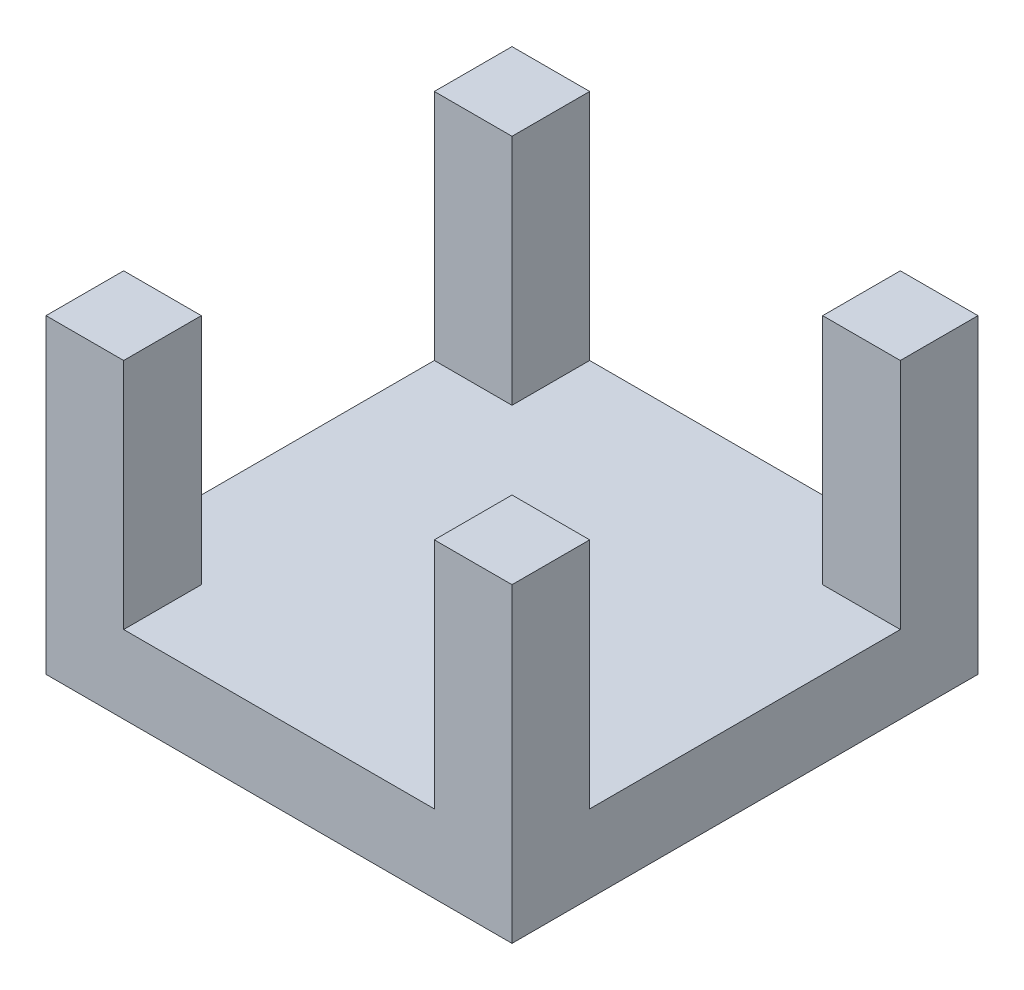
SolidWorks part; units mm, degrees
ref_plane "前视基准面" through (0, 0, 0) normal (0, 0, 1) x (1, 0, 0)
ref_plane "上视基准面" through (0, 0, 0) normal (0, 1, 0) x (1, 0, 0)
ref_plane "右视基准面" through (0, 0, 0) normal (1, 0, 0) x (0, 0, -1)
other "Configuration Table"
sketch "草图1" plane through (0, 0, 0) normal (0, 1, 0) x (1, 0, 0)
  line L1 (-300, 300) -> (300, 300)
  line L2 (-300, 300) -> (-300, -300)
  line L3 (-300, -300) -> (300, -300)
  line L4 (300, 300) -> (300, -300)
  dimension "D1" = 600
  dimension "D2" = 600
  dimension "D3" = 300
  dimension "D4" = 300
extrude "凸台-拉伸1" add sketch "草图1" along normal blind 400
sketch "草图2" plane through (0, 400, 0) normal (0, 1, 0) x (1, 0, 0)
  line L0 (-300, 300) -> (-300, -300) construction
  line L1 (-500, 200) -> (-200, 200)
  line L2 (-500, 200) -> (-500, -200)
  line L3 (-500, -200) -> (-200, -200)
  line L4 (500, 200) -> (500, -200)
  line L5 (-200, 500) -> (200, 500)
  line L6 (-200, 500) -> (-200, 200)
  line L7 (-200, -500) -> (200, -500)
  line L8 (200, 500) -> (200, 200)
  line L9 (300, 300) -> (-300, 300) construction
  line L10 (200, 200) -> (500, 200)
  line L11 (-200, -200) -> (-200, -500)
  line L12 (200, -200) -> (500, -200)
  line L13 (200, -200) -> (200, -500)
  dimension "D1" = 400
  dimension "D2" = 400
  dimension "D3" = 1000
  dimension "D4" = 1000
  dimension "D5" = 100
  dimension "D6" = 100
  dimension "D7" = 200
  dimension "D8" = 200
extrude "切除-拉伸1" cut sketch "草图2" against normal blind 300
sketch "草图3" plane through (0, 0, 0) normal (0, -1, 0) x (1, 0, 0)
  line L0 (-300, -300) -> (-300, 300) construction
  circle A0 centre (0, -200) radius 50
  circle A1 centre (0, -200) radius 60
  dimension "D1" = 100
  dimension "D2" = 120
  dimension "D3" = 200
  dimension "D4" = 300
extrude "凸台-拉伸2" add sketch "草图3" along normal blind 10
